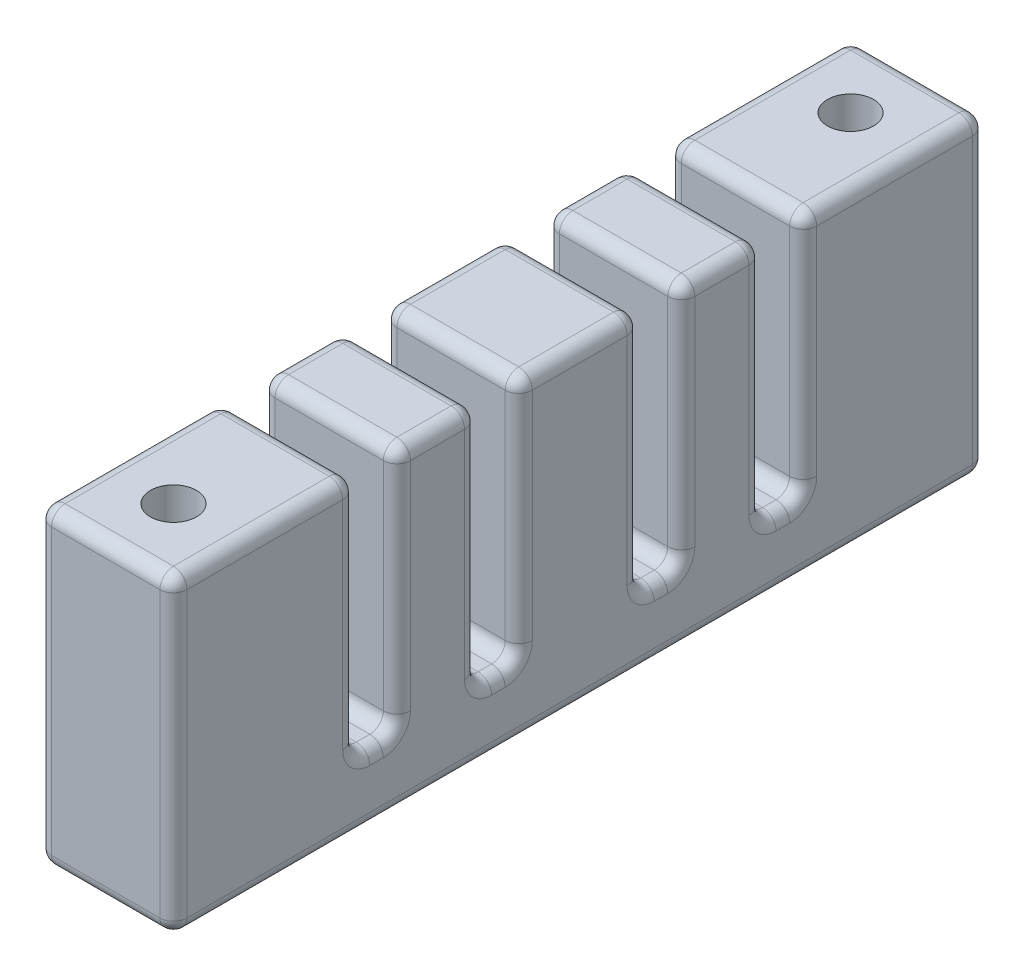
SolidWorks part; units mm, degrees
ref_plane "Front Plane" through (0, 0, 0) normal (0, 0, 1) x (1, 0, 0)
ref_plane "Top Plane" through (0, 0, 0) normal (0, 1, 0) x (1, 0, 0)
ref_plane "Right Plane" through (0, 0, 0) normal (1, 0, 0) x (0, 0, -1)
sketch "Sketch1" plane through (0, 0, 0) normal (0, 1, 0) x (1, 0, 0)
  line L0 (0, 25) -> (0, -25) construction
  line L1 (5, -30) -> (-5, -30)
  line L2 (5, -30) -> (5, 30)
  line L3 (5, 30) -> (-5, 30)
  line L4 (-5, -30) -> (-5, 30)
  line L5 (5, -30) -> (-5, 30) construction
  line L6 (5, 30) -> (-5, -30) construction
  circle A0 centre (0, 25) radius 1.7
  circle A1 centre (0, -25) radius 1.7
  point P0 (0, 0)
  point P8 (0, 0)
  dimension "D4" = 3.4
  dimension "D1" = 60
  dimension "D2" = 10
  dimension "D3" = 50
extrude "Boss-Extrude1" add sketch "Sketch1" along normal blind 5
sketch "Sketch2" plane through (0, 5, 0) normal (0, 1, 0) x (1, 0, 0)
  line L0 (5, 13.5) -> (5, 7.5)
  line L1 (5, -30) -> (5, 30) construction
  line L2 (-5, -4.5) -> (5, -4.5)
  line L3 (-5, -4.5) -> (-5, 4.5)
  line L4 (-5, 4.5) -> (5, 4.5)
  line L5 (5, -4.5) -> (5, 4.5)
  line L6 (-5, -4.5) -> (5, 4.5) construction
  line L7 (-5, 4.5) -> (5, -4.5) construction
  line L8 (-5, 30) -> (-5, -30) construction
  line L9 (-5, 30) -> (5, 30)
  line L10 (-5, 30) -> (-5, 16.5)
  line L11 (-5, 7.5) -> (5, 7.5)
  line L12 (5, 30) -> (5, 16.5)
  line L13 (5, -30) -> (-5, -30)
  line L14 (5, -30) -> (5, -16.5)
  line L15 (5, -7.5) -> (-5, -7.5)
  line L16 (-5, -30) -> (-5, -16.5)
  line L17 (-5, -13.5) -> (5, -13.5)
  line L19 (-5, -16.5) -> (5, -16.5)
  line L21 (-5, 13.5) -> (5, 13.5)
  line L23 (-5, 16.5) -> (5, 16.5)
  line L25 (-5, 13.5) -> (-5, 7.5)
  line L26 (5, -13.5) -> (5, -7.5)
  line L27 (-5, -13.5) -> (-5, -7.5)
  circle A0 centre (0, -25) radius 1.7 construction
  circle A1 centre (0, 25) radius 1.7 construction
  circle A2 centre (0, -25) radius 1.7
  circle A3 centre (0, 25) radius 1.7
  point P6 (0, 0)
  dimension "D1" = 9
  dimension "D2" = 3
  dimension "D3" = 3
  dimension "D4" = 3
  dimension "D5" = 6
  dimension "D6" = 6
  dimension "D7" = 3
extrude "Boss-Extrude2" add sketch "Sketch2" along normal blind 18
fillet "Fillet1" radius 1 60 edges at (0, 23, -30) (0, 0, -30) (0, 23, 7.5) (0, 5, 7.5) (0, 23, 4.5) (0, 5, 4.5) (0, 23, -4.5) (0, 5, -4.5) (0, 23, -7.5) (0, 5, -7.5) (-5, 11.5, -30) (-5, 23, -10.5) (-5, 23, -23.25) (-5, 14, -7.5) (-5, 5, -6) (-5, 14, -4.5) (-5, 23, 0) (-5, 14, 4.5) (-5, 5, 6) (-5, 14, 7.5) (-5, 23, 23.25) (-5, 23, 10.5) (-5, 0, 0) (5, 23, 10.5) (5, 23, 23.25) (5, 14, 7.5) (5, 5, 6) (5, 14, 4.5) (5, 23, 0) (5, 14, -4.5) (5, 5, -6) (5, 14, -7.5) (5, 23, -23.25) (5, 23, -10.5) (5, 11.5, -30) (5, 0, 0) (-5, 11.5, 30) (0, 23, 30) (5, 11.5, 30) (0, 0, 30) (-5, 14, -16.5) (-5, 5, -15) (-5, 14, -13.5) (-5, 14, 13.5) (-5, 5, 15) (-5, 14, 16.5) (5, 14, 16.5) (5, 5, 15) (5, 14, 13.5) (5, 14, -13.5) (5, 5, -15) (5, 14, -16.5) (0, 23, 16.5) (0, 5, 16.5) (0, 23, -13.5) (0, 5, -13.5) (0, 23, -16.5) (0, 5, -16.5) (0, 23, 13.5) (0, 5, 13.5)
